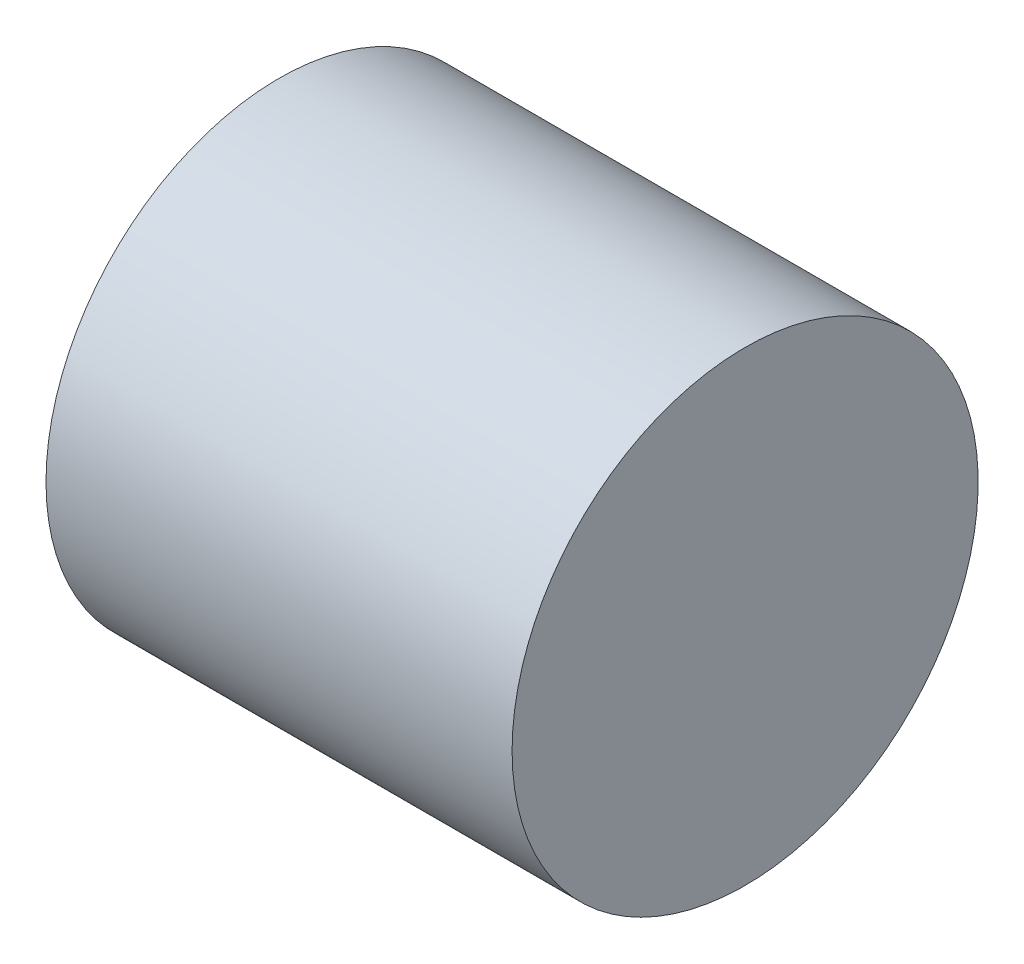
SolidWorks part; units mm, degrees
ref_plane "Plan1" through (0, 0, 0) normal (0, 0, 1) x (1, 0, 0)
ref_plane "Plan2" through (0, 0, 0) normal (0, 1, 0) x (1, 0, 0)
ref_plane "Plan3" through (0, 0, 0) normal (1, 0, 0) x (0, 0, -1)
sketch "Esquisse1" plane through (0, 0, 0) normal (0, 0, 1) x (1, 0, 0)
  line L0 (-4.4762, 20) -> (2.5238, 20)
  line L2 (-4.4762, 20) -> (-4.4762, 23.5)
  line L3 (2.5238, 23.5) -> (-4.4762, 23.5)
  line L4 (2.5238, 23.5) -> (2.5238, 20)
  line L5 (-6.3552, 23.5) -> (3.5768, 23.5) construction
revolve "Base-Révolution" add sketch "Esquisse1" angle 360 about L5
